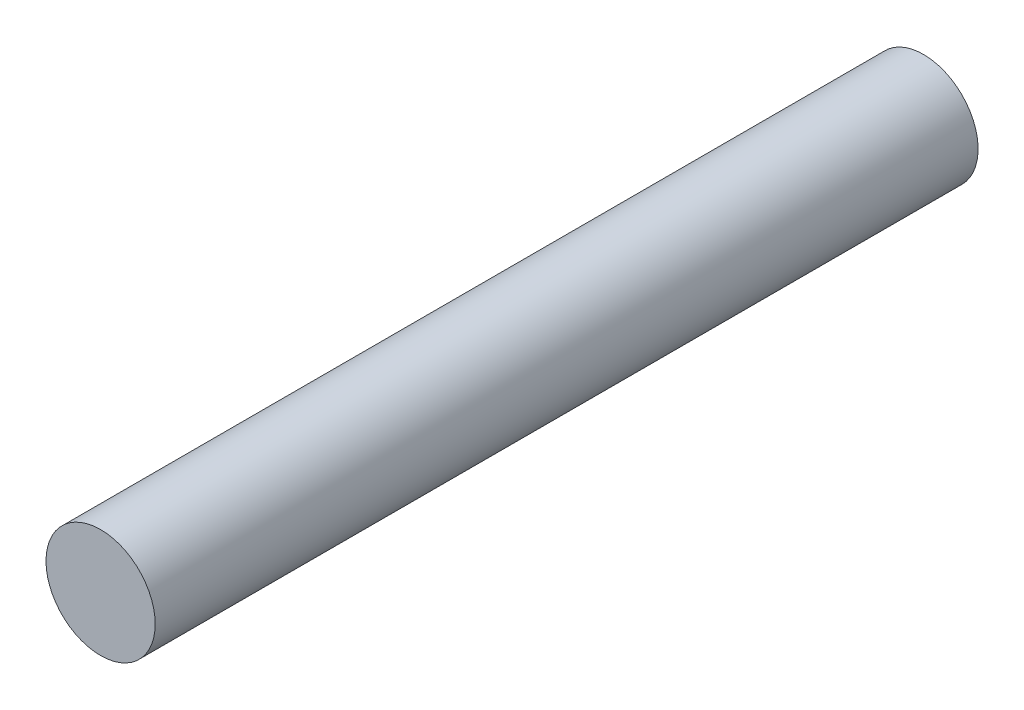
SolidWorks part; units mm, degrees
material "1.7036 (28CrS4)"
ref_plane "정면" through (0, 0, 0) normal (0, 0, 1) x (1, 0, 0)
ref_plane "윗면" through (0, 0, 0) normal (0, 1, 0) x (1, 0, 0)
ref_plane "우측면" through (0, 0, 0) normal (1, 0, 0) x (0, 0, -1)
sketch "스케치1" plane through (0, 0, 0) normal (0, 0, 1) x (1, 0, 0)
  circle A0 centre (0, 0) radius 20
  dimension "D1" = 40
extrude "보스-돌출1" add sketch "스케치1" along normal blind 266.5
sketch "스케치2" plane through (0, 0, 266.5) normal (0, 0, 1) x (1, 0, 0)
  text T0 "TEST\r\n"
sketch "스케치3" plane through (0, 0, 0) normal (0, 0, -1) x (-1, 0, 0)
  circle A0 centre (0, 0) radius 20
extrude "보스-돌출2" add sketch "스케치3" along normal blind 35
sketch "스케치4" plane through (0, 0, -35) normal (0, 0, -1) x (-1, 0, 0)
  line L0 (-3.5157, 3.5553) -> (-3.4843, -3.5861)
  arc A0 (-3.4843, -3.5861) -> (-3.5157, 3.5553) centre (0, 0) ccw
  dimension "D1" = 5
  dimension "D2" = 3.5
  dimension "D3" = 7.1414
extrude "컷-돌출1" cut sketch "스케치4" against normal blind 25
sketch "스케치5" plane through (0, 0, -35) normal (0, 0, -1) x (-1, 0, 0)
  circle A0 centre (0, 0) radius 5
extrude "컷-돌출2" cut sketch "스케치5" against normal blind 10
equation "\"`\"=4"
